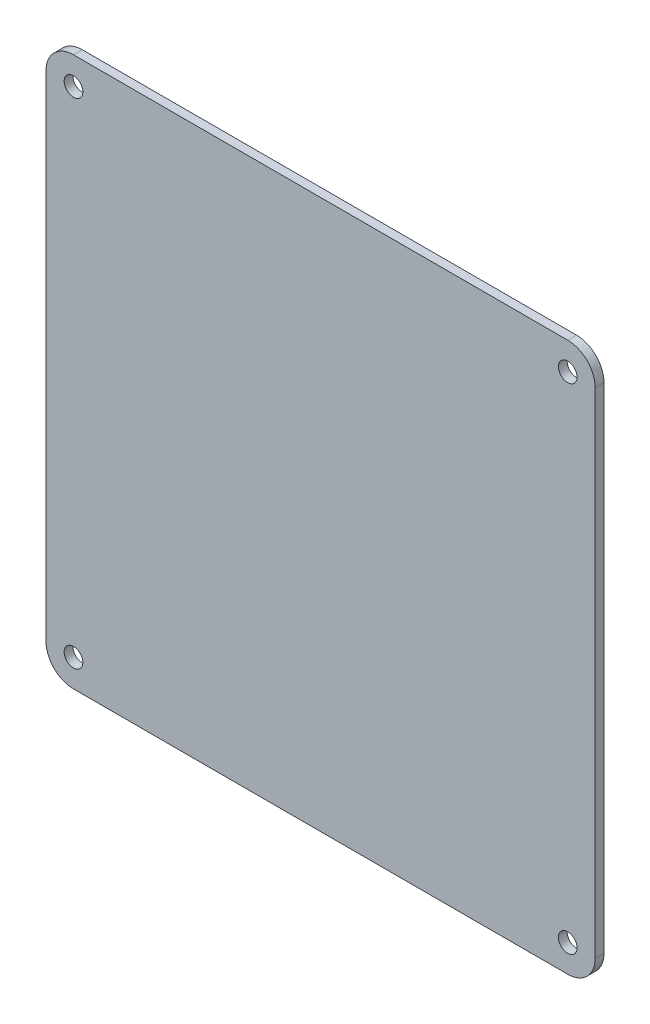
SolidWorks part; units mm, degrees
ref_plane "1" through (0, 0, 0) normal (0, 0, 1) x (1, 0, 0)
ref_plane "2" through (0, 0, 0) normal (0, 1, 0) x (1, 0, 0)
ref_plane "3" through (0, 0, 0) normal (1, 0, 0) x (0, 0, -1)
ref_plane "Front Plane" through (0, 0, 0) normal (0, -1, 0) x (1, 0, 0)
ref_plane "Right Plane" through (0, 0, 0) normal (1, 0, 0) x (0, 1, 0)
ref_plane "Top Plane" through (0, 0, 0) normal (0, 0, 1) x (1, 0, 0)
ref_plane "Plane1" through (0, 0, 1.6) normal (0, 0, 1) x (1, 0, 0)
sketch "Sketch1" plane through (0, 0, 0) normal (0, 0, 1) x (1, 0, 0)
  line L0 (-50, 50) -> (50, 50) construction
  line L1 (-50, 50) -> (-50, -50) construction
  line L2 (50, 50) -> (50, -50) construction
  line L3 (-50, -50) -> (50, -50) construction
  line L4 (0, 50) -> (0, 5.152) construction
  line L5 (50, 0) -> (24.8253, 0) construction
  line L6 (-45, 45) -> (45, 45) construction
  line L7 (45, 45) -> (45, -45) construction
  line L8 (-45, -45) -> (45, -45) construction
  line L9 (-45, 45) -> (-45, -45) construction
  circle A0 centre (45, 45) radius 1.5 construction
  circle A1 centre (-45, 45) radius 1.5 construction
  circle A2 centre (-45, -45) radius 1.5 construction
  circle A3 centre (45, -45) radius 1.5 construction
  dimension "D4" = 3
  dimension "D1" = 100
  dimension "D2" = 100
  dimension "D3" = 5
sketch "Sketch2" plane through (0, 0, 0) normal (0, 0, 1) x (1, 0, 0)
  line L0 (-45, 50) -> (45, 50)
  line L1 (-50, 45) -> (-50, -45)
  line L2 (50, 45) -> (50, -45)
  line L3 (-45, -50) -> (45, -50)
  line L4 (-50, 50) -> (50, 50) construction
  line L5 (-50, 50) -> (-50, -50) construction
  line L6 (-50, -50) -> (50, -50) construction
  line L7 (50, 50) -> (50, -50) construction
  arc A0 (50, -45) -> (45, -50) centre (45, -45) cw
  arc A1 (-50, -45) -> (-45, -50) centre (-45, -45) ccw
  arc A2 (-50, 45) -> (-45, 50) centre (-45, 45) cw
  arc A3 (45, 50) -> (50, 45) centre (45, 45) cw
  dimension "D1" = 5
extrude "Boss-Extrude1" add sketch "Sketch2" along normal blind 1.6
hole_wizard "M3 Clearance Hole1" positions "Sketch3" profile "Sketch5" hole size "M3" standard "ANSI Metric" end condition through all
sketch "Sketch3" plane through (0, 0, 1.6) normal (0, 0, 1) x (1, 0, 0)
  circle A0 centre (45, 45) radius 1.5 construction
  circle A1 centre (-45, 45) radius 1.5 construction
  circle A2 centre (-45, -45) radius 1.5 construction
  circle A3 centre (45, -45) radius 1.5 construction
  point P0 (45, 45)
  point P2 (-45, 45)
  point P4 (-45, -45)
  point P6 (45, -45)
sketch "Sketch5" plane through (45, 45, 1.6) normal (1, 0, 0) x (0, -1, 0)
  line L0 (0, 0) -> (0, 1.6)
  line L1 (0, 1.6) -> (1.7, 1.6)
  line L2 (1.7, 1.6) -> (1.7, 0)
  line L5 (1.7, 0) -> (0, 0)
  line L11 (0, -6.35) -> (0, 107.95) construction
  dimension "Thru Hole Dia." = 3.4
  dimension "Thru Hole Depth" = 1.6
